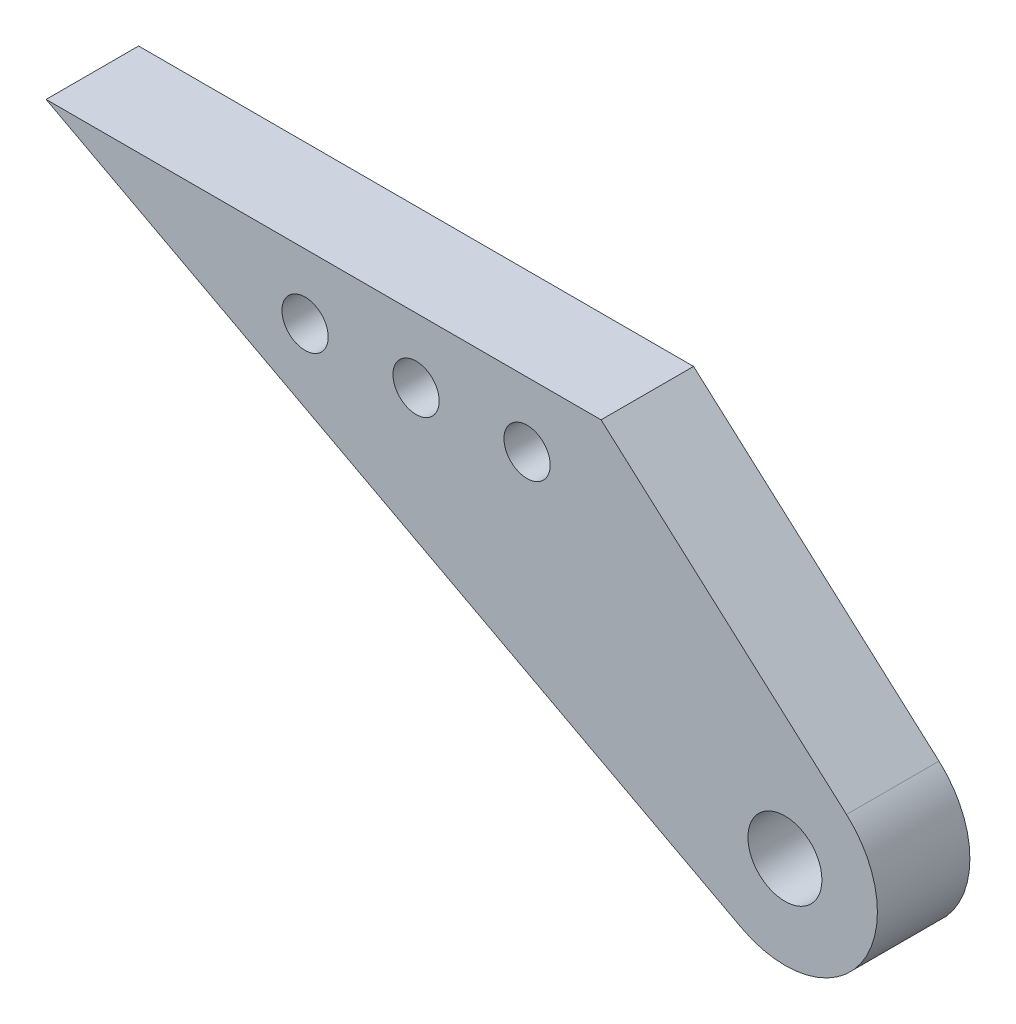
SolidWorks part; units mm, degrees
ref_plane "前视基准面" through (0, 0, 0) normal (0, 0, 1) x (1, 0, 0)
ref_plane "上视基准面" through (0, 0, 0) normal (0, 1, 0) x (1, 0, 0)
ref_plane "右视基准面" through (0, 0, 0) normal (1, 0, 0) x (0, 0, -1)
other "Configuration Table"
sketch "草图2" plane through (0, 0, 0) normal (0, 0, 1) x (1, 0, 0)
  line L0 (-30, 0) -> (0, 0)
  line L2 (7.5907, -19.9873) -> (-30, 0)
  line L5 (0, 0) -> (13.2676, -11.8424)
  circle A2 centre (-4, -3.5) radius 1.25
  arc A3 (7.5907, -19.9873) -> (13.2676, -11.8424) centre (9.9381, -15.5726) ccw
  circle A4 centre (9.9381, -15.5726) radius 2
  circle A5 centre (-10, -3.5) radius 1.25
  circle A6 centre (-16, -3.5) radius 1.25
  point P3 (9.9381, -15.5726)
  dimension "D5" = 2.5
  dimension "D6" = 3
  dimension "D4" = 3.5
  dimension "D8" = 4
  dimension "D9" = 5
  dimension "D1" = 4
  dimension "D2" = 28
  dimension "D3" = 30
extrude "凸台-拉伸1" add sketch "草图2" along normal blind 5
